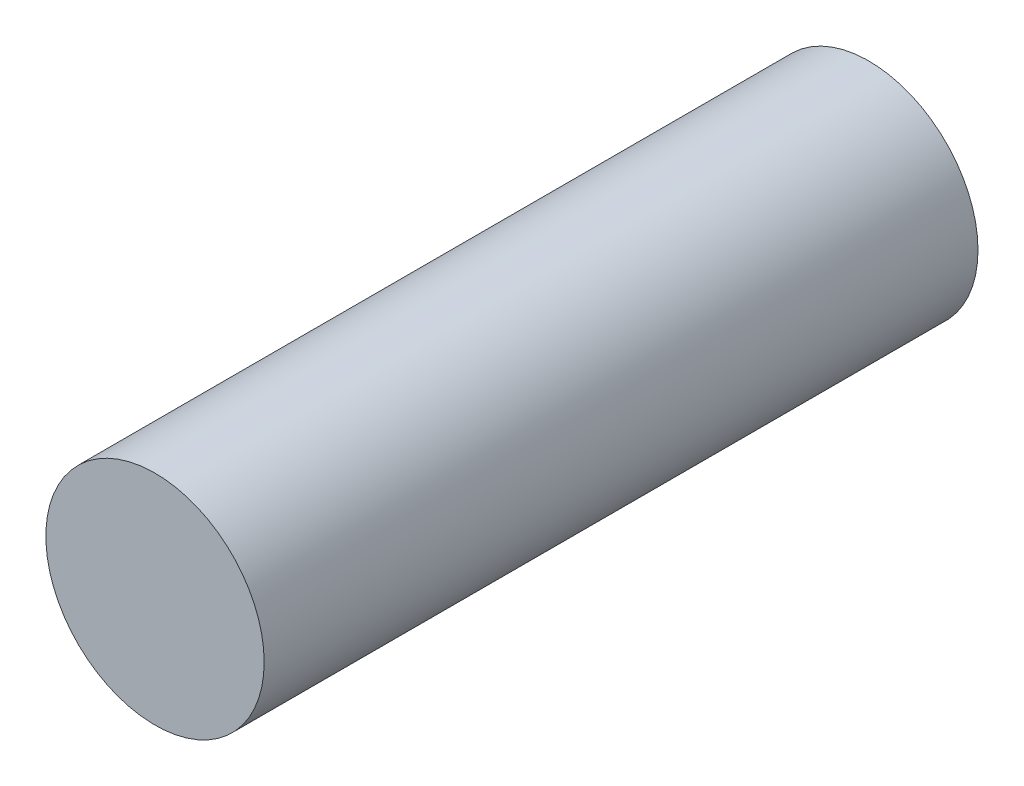
SolidWorks part; units mm, degrees
ref_plane "Front Plane" through (0, 0, 0) normal (0, 0, 1) x (1, 0, 0)
ref_plane "Top Plane" through (0, 0, 0) normal (0, 1, 0) x (1, 0, 0)
ref_plane "Right Plane" through (0, 0, 0) normal (1, 0, 0) x (0, 0, -1)
sketch "Sketch2" plane through (0, 0, 0) normal (0, 0, 1) x (1, 0, 0)
  circle A0 centre (0, 0) radius 3.175
  dimension "D1" = 6.35
extrude "Boss-Extrude1" add sketch "Sketch2" along normal blind 20.762
